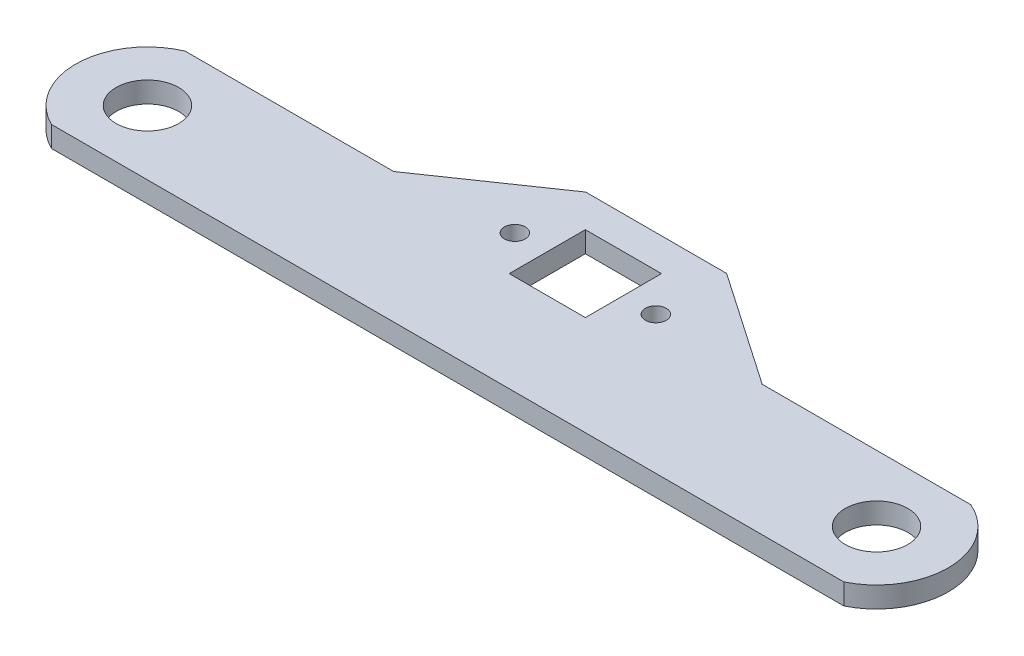
SolidWorks part; units mm, degrees
ref_plane "Front Plane" through (0, 0, 0) normal (0, 0, 1) x (1, 0, 0)
ref_plane "Top Plane" through (0, 0, 0) normal (0, 1, 0) x (1, 0, 0)
ref_plane "Right Plane" through (0, 0, 0) normal (1, 0, 0) x (0, 0, -1)
sketch "Sketch1" plane through (0, 0, 0) normal (0, 1, 0) x (1, 0, 0)
  line L0 (0, -1000) -> (0, 49000) construction
  line L1 (48.26, 0) -> (-48.26, 0)
  line L2 (-47.8442, 15.875) -> (-22.4442, 15.875)
  line L3 (-22.4442, 15.875) -> (-8.5852, 25.4)
  line L4 (-8.5852, 25.4) -> (8.5852, 25.4)
  line L5 (22.4442, 15.875) -> (8.5852, 25.4)
  line L6 (47.8442, 15.875) -> (22.4442, 15.875)
  line L7 (-55, 0) -> (55, 0) construction
  line L8 (0, -55) -> (0, 55) construction
  line L9 (-4.6355, 21.4122) -> (4.6355, 21.4122)
  line L10 (-4.6355, 21.4122) -> (-4.6355, 12.1412)
  line L11 (-4.6355, 12.1412) -> (4.6355, 12.1412)
  line L12 (4.6355, 21.4122) -> (4.6355, 12.1412)
  arc A0 (-48.26, 0) -> (-47.8442, 15.875) centre (-44.4016, 7.8419) cw
  arc A1 (48.26, 0) -> (47.8442, 15.875) centre (44.4016, 7.8419) ccw
  circle A2 centre (-8.5852, 16.7767) radius 1.27
  circle A3 centre (8.5852, 16.7767) radius 1.27
  circle A4 centre (-44.4016, 7.8419) radius 3.81
  circle A5 centre (44.4016, 7.8419) radius 3.81
  point P14 (0, 25.4)
  point P15 (0, 0)
  point P21 (0, 21.4122)
  point P28 (-4.6355, 16.7767)
  dimension "D1" = 96.52
  dimension "D2" = 2.54
  dimension "D10" = 7.62
  dimension "D3" = 9.271
  dimension "D4" = 9.271
  dimension "D5" = 17.1704
  dimension "D6" = 25.4
  dimension "D7" = 3.9878
  dimension "D8" = 25.4
  dimension "D9" = 15.875
extrude "Boss-Extrude1" add sketch "Sketch1" along normal blind 2.54
